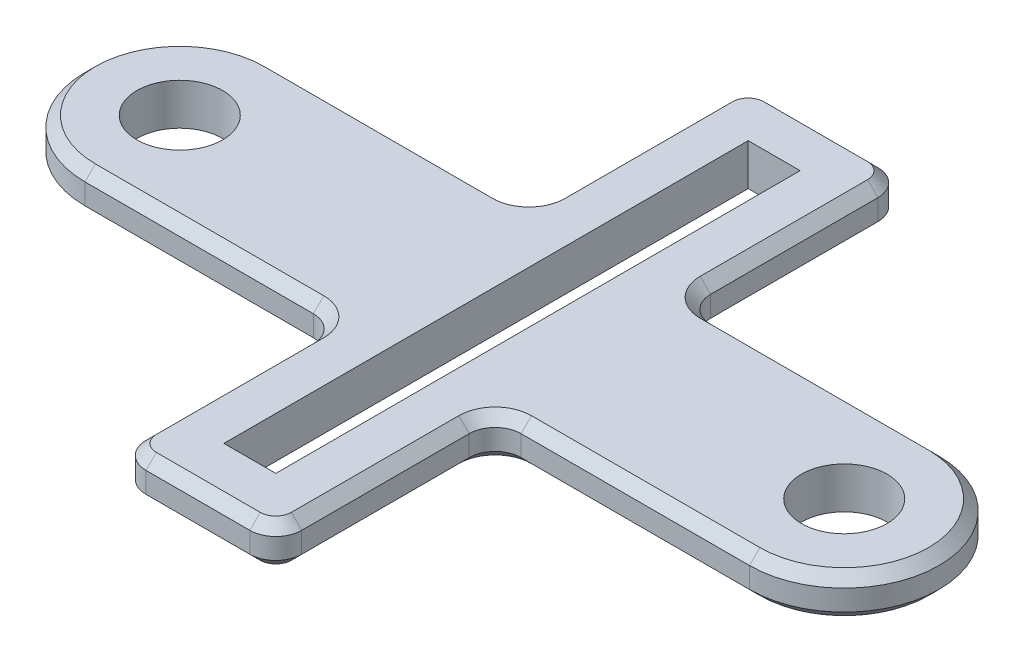
SolidWorks part; units mm, degrees
ref_plane "Front Plane" through (0, 0, 0) normal (0, 0, 1) x (1, 0, 0)
ref_plane "Top Plane" through (0, 0, 0) normal (0, 1, 0) x (1, 0, 0)
ref_plane "Right Plane" through (0, 0, 0) normal (1, 0, 0) x (0, 0, -1)
sketch "Sketch1" plane through (0, 0, 0) normal (0, 1, 0) x (1, 0, 0)
  line L0 (0, 38.3905) -> (0, -23.0868) construction
  line L1 (-32, 20.25) -> (32, 20.25) construction
  line L2 (2.5, -25.25) -> (-2.5, -25.25)
  line L3 (2.5, -25.25) -> (2.5, 25.25)
  line L4 (2.5, 25.25) -> (-2.5, 25.25)
  line L5 (-2.5, -25.25) -> (-2.5, 25.25)
  line L6 (2.5, -25.25) -> (-2.5, 25.25) construction
  line L7 (2.5, 25.25) -> (-2.5, -25.25) construction
  line L8 (-32, -20.25) -> (32, -20.25) construction
  line L9 (-32, 9.125) -> (-7.5, 9.125)
  line L10 (-7.5, 9.125) -> (-7.5, 30.25)
  line L11 (-7.5, 30.25) -> (7.5, 30.25)
  line L12 (7.5, 9.125) -> (7.5, 30.25)
  line L13 (32, 9.125) -> (7.5, 9.125)
  line L14 (-62.6027, 0) -> (68.4609, 0) construction
  line L15 (32, -9.125) -> (7.5, -9.125)
  line L16 (7.5, -9.125) -> (7.5, -30.25)
  line L17 (-7.5, -30.25) -> (7.5, -30.25)
  line L18 (-7.5, -9.125) -> (-7.5, -30.25)
  line L19 (-32, -9.125) -> (-7.5, -9.125)
  circle A0 centre (-32, 0) radius 4.125
  circle A1 centre (32, 0) radius 4.125
  circle A2 centre (-32, 0) radius 20.25 construction
  circle A3 centre (32, 0) radius 20.25 construction
  arc A4 (-32, 9.125) -> (-32, -9.125) centre (-32, 0) ccw
  arc A5 (32, -9.125) -> (32, 9.125) centre (32, 0) ccw
  point P7 (0, 0)
  point P30 (0, 30.25)
  dimension "D2" = 8.25
  dimension "D3" = 40.5
  dimension "D6" = 18.25
  dimension "D1" = 64
  dimension "D4" = 5
  dimension "D5" = 50.5
  dimension "D7" = 5
  dimension "D8" = 5
extrude "Boss-Extrude1" add sketch "Sketch1" along normal blind 4
fillet "Fillet1" radius 2.5 8 edges at (-7.5, 2, 9.125) (-7.5, 2, 30.25) (7.5, 2, 30.25) (7.5, 2, 9.125) (7.5, 2, -9.125) (7.5, 2, -30.25) (-7.5, 2, -30.25) (-7.5, 2, -9.125)
chamfer "Chamfer1" distance 1 angle 45 40 edges at (-7.5, 4, 19.6875) (-6.7678, 4, 29.5178) (-8.2322, 4, 9.8572) (0, 4, 30.25) (-21, 4, 9.125) (6.7678, 4, 29.5178) (-41.125, 4, 0) (7.5, 4, 19.6875) (-21, 4, -9.125) (8.2322, 4, 9.8572) (-8.2322, 4, -9.8572) (21, 4, 9.125) (-7.5, 4, -19.6875) (41.125, 4, 0) (-6.7678, 4, -29.5178) (21, 4, -9.125) (0, 4, -30.25) (8.2322, 4, -9.8572) (6.7678, 4, -29.5178) (7.5, 4, -19.6875) (21, 0, 9.125) (41.125, 0, 0) (8.2322, 0, 9.8572) (21, 0, -9.125) (7.5, 0, 19.6875) (8.2322, 0, -9.8572) (6.7678, 0, 29.5178) (7.5, 0, -19.6875) (0, 0, 30.25) (6.7678, 0, -29.5178) (-6.7678, 0, 29.5178) (0, 0, -30.25) (-7.5, 0, 19.6875) (-6.7678, 0, -29.5178) (-8.2322, 0, 9.8572) (-7.5, 0, -19.6875) (-21, 0, 9.125) (-8.2322, 0, -9.8572) (-41.125, 0, 0) (-21, 0, -9.125)
